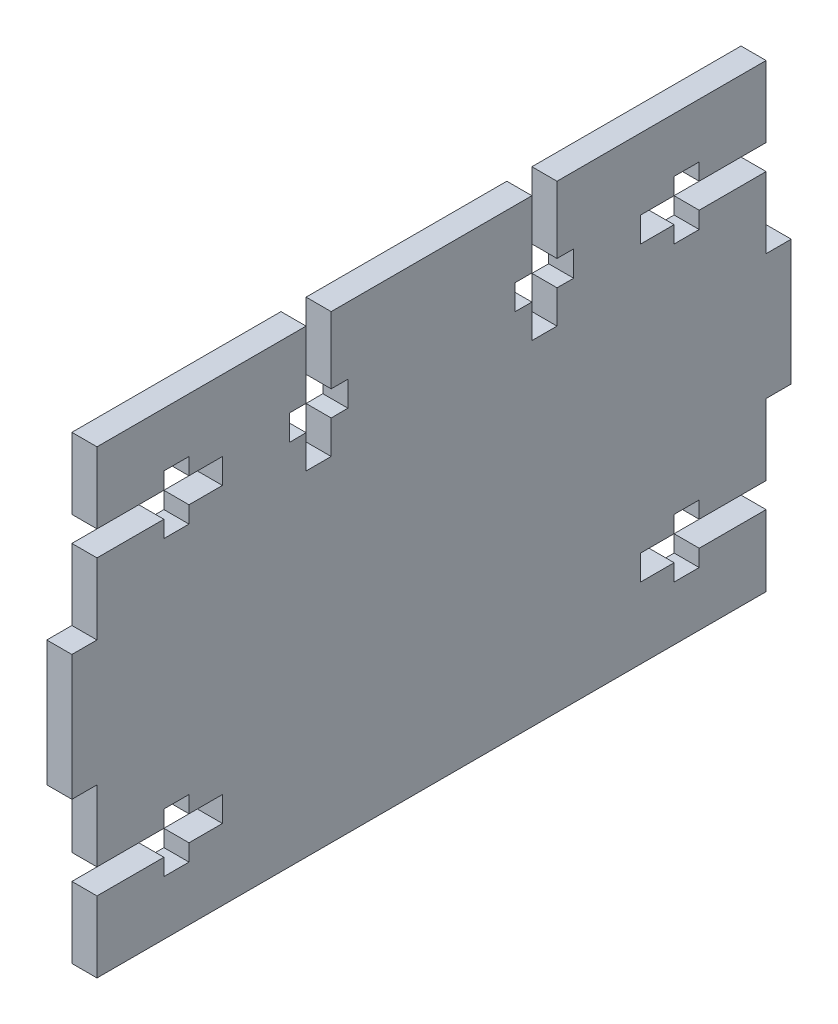
SolidWorks part; units mm, degrees
ref_plane "Front" through (0, 0, 0) normal (0, 0, 1) x (1, 0, 0)
ref_plane "Top" through (0, 0, 0) normal (0, 1, 0) x (1, 0, 0)
ref_plane "Right" through (0, 0, 0) normal (1, 0, 0) x (0, 0, -1)
sketch "Croquis1" plane through (0, 0, 0) normal (1, 0, 0) x (0, 0, -1)
  line L0 (0, 0) -> (0, -28.3319) construction
  line L1 (-40, 0) -> (40, 0)
  line L2 (40, 0) -> (40, -20)
  line L3 (40, -20) -> (43, -20)
  line L4 (43, -20) -> (43, -35)
  line L5 (43, -35) -> (40, -35)
  line L6 (40, -35) -> (40, -55)
  line L7 (40, -55) -> (-40, -55)
  line L8 (-40, -35) -> (-40, -55)
  line L9 (-43, -35) -> (-40, -35)
  line L10 (-43, -20) -> (-43, -35)
  line L11 (-40, -20) -> (-43, -20)
  line L12 (-40, 0) -> (-40, -20)
  point P11 (0, -55)
  dimension "D1" = 40
  dimension "D2" = 3
  dimension "D3" = 15
  dimension "D4" = 20
  dimension "D5" = 20
  dimension "D6" = 3
extrude "Saliente-Extruir1" add sketch "Croquis1" along normal blind 3
sketch "Croquis2" plane through (0, 0, 0) normal (-1, 0, 0) x (0, 0, 1)
  line L0 (-40, -20) -> (-40, 0) construction
  line L1 (-40, -8.5) -> (-32, -8.5)
  line L2 (-40, -8.5) -> (-40, -11.5)
  line L3 (-40, -11.5) -> (-32, -11.5)
  line L4 (-25, -8.5) -> (-25, -11.5)
  line L5 (-32, -11.5) -> (-32, -13.5)
  line L6 (-29, -8.5) -> (-25, -8.5)
  line L7 (-29, -11.5) -> (-29, -13.5)
  line L8 (-29, -6.5) -> (-32, -6.5)
  line L9 (-29, -6.5) -> (-29, -8.5)
  line L10 (-29, -13.5) -> (-32, -13.5)
  line L11 (-32, -6.5) -> (-32, -8.5)
  line L12 (-29, -11.5) -> (-25, -11.5)
  line L13 (0, 0) -> (0, -30.415) construction
  line L14 (29, -11.5) -> (25, -11.5)
  line L15 (32, -6.5) -> (32, -8.5)
  line L16 (29, -13.5) -> (32, -13.5)
  line L17 (29, -6.5) -> (29, -8.5)
  line L18 (29, -6.5) -> (32, -6.5)
  line L19 (29, -11.5) -> (29, -13.5)
  line L20 (29, -8.5) -> (25, -8.5)
  line L21 (32, -11.5) -> (32, -13.5)
  line L22 (25, -8.5) -> (25, -11.5)
  line L23 (40, -11.5) -> (32, -11.5)
  line L24 (40, -8.5) -> (40, -11.5)
  line L25 (40, -8.5) -> (32, -8.5)
  line L26 (-12, 0) -> (-12, -8)
  line L27 (-12, 0) -> (-15, 0)
  line L28 (-15, 0) -> (-15, -8)
  line L29 (-12, -15) -> (-15, -15)
  line L30 (-15, -8) -> (-17, -8)
  line L31 (-12, -11.0138) -> (-12, -15)
  line L32 (-15, -11.0346) -> (-17, -11.0484)
  line L33 (-10, -11) -> (-10, -8)
  line L34 (-10, -11) -> (-12, -11.0138)
  line L35 (-17, -11.0484) -> (-17, -8)
  line L36 (-10, -8) -> (-12, -8)
  line L37 (-15, -11.0346) -> (-15, -15)
  line L38 (-40, 0) -> (40, 0) construction
  line L39 (15, -11.0346) -> (15, -15)
  line L40 (10, -8) -> (12, -8)
  line L41 (17, -11.0484) -> (17, -8)
  line L42 (10, -11) -> (12, -11.0138)
  line L43 (10, -11) -> (10, -8)
  line L44 (15, -11.0346) -> (17, -11.0484)
  line L45 (12, -11.0138) -> (12, -15)
  line L46 (15, -8) -> (17, -8)
  line L47 (12, -15) -> (15, -15)
  line L48 (15, 0) -> (15, -8)
  line L49 (12, 0) -> (15, 0)
  line L50 (12, 0) -> (12, -8)
  line L51 (-43, -27.5) -> (43, -27.5) construction
  line L52 (-43, -35) -> (-43, -20) construction
  line L53 (43, -20) -> (43, -35) construction
  line L54 (40, -46.5) -> (32, -46.5)
  line L55 (40, -46.5) -> (40, -43.5)
  line L56 (40, -43.5) -> (32, -43.5)
  line L57 (25, -46.5) -> (25, -43.5)
  line L58 (32, -43.5) -> (32, -41.5)
  line L59 (29, -46.5) -> (25, -46.5)
  line L60 (29, -43.5) -> (29, -41.5)
  line L61 (29, -48.5) -> (32, -48.5)
  line L62 (29, -48.5) -> (29, -46.5)
  line L63 (29, -41.5) -> (32, -41.5)
  line L64 (32, -48.5) -> (32, -46.5)
  line L65 (29, -43.5) -> (25, -43.5)
  line L66 (-29, -43.5) -> (-25, -43.5)
  line L67 (-32, -48.5) -> (-32, -46.5)
  line L68 (-29, -41.5) -> (-32, -41.5)
  line L69 (-29, -48.5) -> (-29, -46.5)
  line L70 (-29, -48.5) -> (-32, -48.5)
  line L71 (-29, -43.5) -> (-29, -41.5)
  line L72 (-29, -46.5) -> (-25, -46.5)
  line L73 (-32, -43.5) -> (-32, -41.5)
  line L74 (-25, -46.5) -> (-25, -43.5)
  line L75 (-40, -43.5) -> (-32, -43.5)
  line L76 (-40, -46.5) -> (-40, -43.5)
  line L77 (-40, -46.5) -> (-32, -46.5)
  point P4 (-35.5, -10)
  point P11 (-33.5, -10)
  point P31 (33.5, -10)
  point P32 (35.5, -10)
  point P37 (-10, -9.5)
  point P38 (-14.383, -9.5)
  point P43 (-13.5, -9.5)
  point P64 (13.5, -9.5)
  point P65 (14.383, -9.5)
  point P84 (35.5, -45)
  point P85 (33.5, -45)
  point P98 (-33.5, -45)
  point P99 (-35.5, -45)
  dimension "D1" = 8
  dimension "D2" = 3
  dimension "D3" = 7
  dimension "D4" = 3
  dimension "D5" = 15
  dimension "D6" = 10
  dimension "D7" = 8.5
  dimension "D8" = 3.5
  dimension "D9" = 8
  dimension "D10" = 3
  dimension "D11" = 3.5
  dimension "D12" = 3
  dimension "D13" = 15
  dimension "D14" = 2
  dimension "D15" = 2
  dimension "D16" = 10
extrude "Cortar-Extruir1" cut sketch "Croquis2" against normal blind 10
